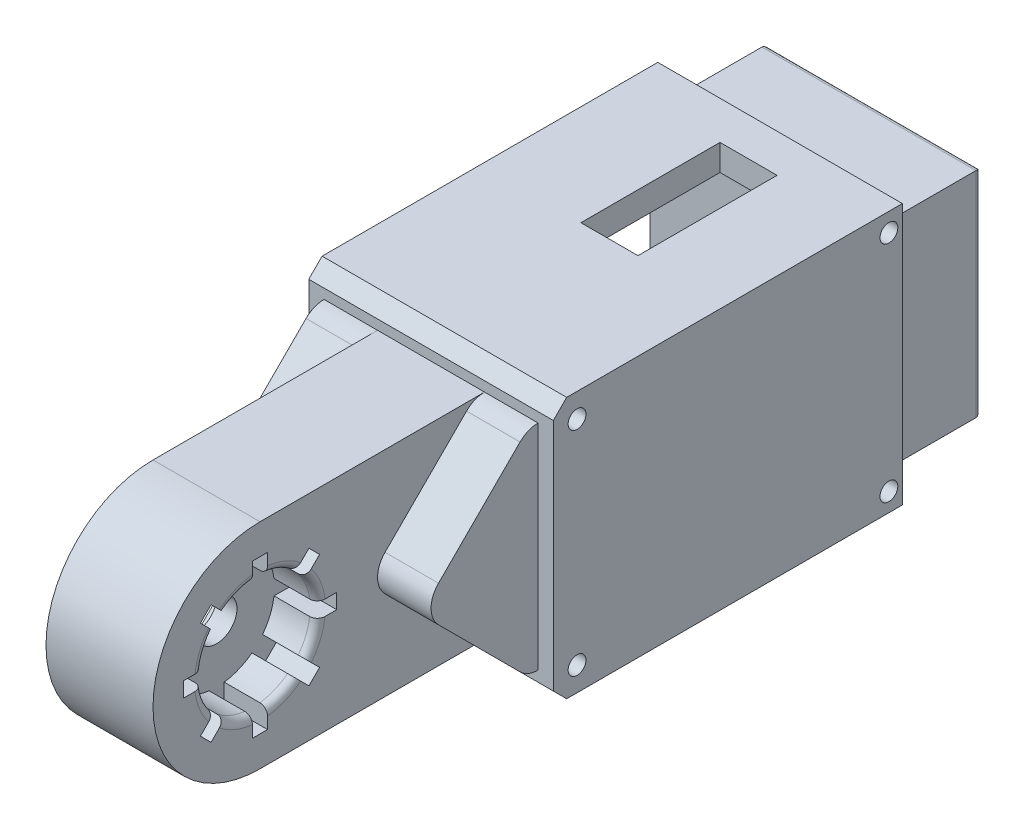
SolidWorks part; units mm, degrees
ref_plane "Front Plane" through (0, 0, 0) normal (0, 0, 1) x (1, 0, 0)
ref_plane "Top Plane" through (0, 0, 0) normal (0, 1, 0) x (1, 0, 0)
ref_plane "Right Plane" through (0, 0, 0) normal (1, 0, 0) x (0, 0, -1)
sketch "Sketch2" plane through (0, 0, 0) normal (0, 0, 1) x (1, 0, 0)
  line L1 (-21, 21) -> (21, 21)
  line L2 (-21, 21) -> (-21, -21)
  line L3 (-21, -21) -> (21, -21)
  line L4 (21, 21) -> (21, -21)
  line L5 (-21, 21) -> (21, -21) construction
  line L6 (-21, -21) -> (21, 21) construction
  point P0 (0, 0)
  dimension "D1" = 42
  dimension "D2" = 42
extrude "Boss-Extrude1" add sketch "Sketch2" along normal blind 89
ref_plane "Plane1" through (0, 0, 89) normal (0, 0, 1) x (1, 0, 0)
sketch "Sketch3" plane through (0, 0, 89) normal (0, 0, 1) x (1, 0, 0)
  line L0 (21, 21) -> (-21, 21) construction
  line L1 (10.5, -21) -> (-10.5, -21)
  line L2 (10.5, -21) -> (10.5, 21)
  line L3 (10.5, 21) -> (-10.5, 21)
  line L4 (-10.5, -21) -> (-10.5, 21)
  line L5 (10.5, -21) -> (-10.5, 21) construction
  line L6 (10.5, 21) -> (-10.5, -21) construction
  point P0 (0, 0)
  dimension "D1" = 21
ref_plane "Plane4" through (0, 0, 0) normal (0, 0, -1) x (-1, 0, 0)
extrude "Boss-Extrude2" add sketch "Sketch3" along normal blind 42
ref_plane "Plane5" through (-10.5, 0, 0) normal (-1, 0, 0) x (0, 0, 1)
sketch "Sketch8" plane through (-10.5, 0, 0) normal (-1, 0, 0) x (0, 0, 1)
  line L0 (131, 21) -> (131, -21) construction
  line L1 (131, 21) -> (131, -21)
  arc A0 (131, 21) -> (131, -21) centre (131, 0) cw
  dimension "D1" = 21
extrude "Boss-Extrude3" add sketch "Sketch8" against normal blind 21
ref_plane "Plane6" through (-10.5, 0, 0) normal (-1, 0, 0) x (0, 0, 1)
sketch "Sketch9" plane through (-10.5, 0, 0) normal (-1, 0, 0) x (0, 0, 1)
  line L0 (89, 21) -> (89, -21) construction
  line L1 (131, 21) -> (131, -21)
  circle A0 centre (131, 0) radius 11.35
  dimension "D1" = 42
  dimension "D2" = 22.7
extrude "Cut-Extrude2" cut sketch "Sketch9" against normal blind 8.5 contours A0
ref_plane "Plane7" through (10.5, 0, 0) normal (1, 0, 0) x (0, 0, -1)
sketch "Sketch11" plane through (10.5, 0, 0) normal (1, 0, 0) x (0, 0, -1)
  line L0 (-131, 21) -> (-131, -21)
  circle A0 centre (-131, 0) radius 11.35
  dimension "D1" = 22.7
extrude "Cut-Extrude3" cut sketch "Sketch11" against normal blind 8.5 contours A0
ref_plane "Plane8" through (-2, 0, 0) normal (-1, 0, 0) x (0, 0, 1)
sketch "Sketch12" plane through (-2, 0, 0) normal (-1, 0, 0) x (0, 0, 1)
  circle A0 centre (131, 0) radius 3.975
  dimension "D1" = 7.95
extrude "Cut-Extrude4" cut sketch "Sketch12" against normal through all
ref_plane "Plane10" through (-2, 0, 0) normal (-1, 0, 0) x (0, 0, 1)
ref_plane "Plane11" through (-10.5, 0, 0) normal (-1, 0, 0) x (0, 0, 1)
sketch "Sketch20" plane through (-10.5, 0, 0) normal (-1, 0, 0) x (0, 0, 1)
  line L0 (131, 0) -> (110, 0)
  line L1 (110, 0) -> (110, 21)
  line L2 (110, 0) -> (110, -21)
  line L4 (110, 21) -> (89, 21)
  line L6 (110, -21) -> (89, -21)
  line L7 (89, 21) -> (110, 0)
  line L8 (89, -21) -> (110, 0)
  line L9 (89, 21) -> (89, -21)
  circle A0 centre (131, 0) radius 11.35
  dimension "D1" = 21
extrude "Boss-Extrude4" add sketch "Sketch20" along normal blind 10.5 and the other way blind 31.5 contours L7 L9 L8
fillet "Fillet1" radius 5 1 edges at (15.75, 0, 110)
fillet "Fillet2" radius 5 1 edges at (-15.75, 0, 110)
fillet "Fillet3" radius 5 1 edges at (-15.75, -21, 89)
fillet "Fillet4" radius 5 1 edges at (-15.75, 21, 89)
fillet "Fillet5" radius 5 1 edges at (15.75, -21, 89)
fillet "Fillet6" radius 5 1 edges at (15.75, 21, 89)
fillet "Fillet7" radius 1.5 1 edges at (-10.5, 0, 142.35)
fillet "Fillet8" radius 1.5 1 edges at (10.5, 0, 119.65)
sketch "Sketch21" plane through (-10.5, 0, 0) normal (-1, 0, 0) x (0, 0, 1)
  line L1 (129.5207, 10.6415) -> (132.4793, 10.6415)
  line L2 (129.5207, 10.6415) -> (129.5207, 15.0585)
  line L3 (129.5207, 15.0585) -> (132.4793, 15.0585)
  line L4 (132.4793, 10.6415) -> (132.4793, 15.0585)
  line L5 (129.5207, 10.6415) -> (132.4793, 15.0585) construction
  line L6 (129.5207, 15.0585) -> (132.4793, 10.6415) construction
  circle A0 centre (131, 0) radius 12.85 construction
  point P0 (131, 12.85)
  dimension "D1" = 4.417
extrude "Cut-Extrude5" cut sketch "Sketch21" against normal blind 8.5
pattern_circular "CirPattern2" count 8 over 360 about axis through (0, 0, 131) along (1, 0, 0) of "Cut-Extrude5"
ref_plane "Plane12" through (0, 21, 0) normal (0, 1, 0) x (1, 0, 0)
ref_plane "Plane13" through (10.5, 0, 0) normal (1, 0, 0) x (0, 0, -1)
ref_plane "Plane14" through (0, 0, 0) normal (1, 0, 0) x (0, 0, -1)
mirror "Mirror1" about plane through (0, 0, 0) normal (1, 0, 0) of "CirPattern2", "Cut-Extrude5"
ref_plane "Plane15" through (21, 0, 0) normal (1, 0, 0) x (0, 0, -1)
sketch "Sketch24" plane through (21, 0, 0) normal (1, 0, 0) x (0, 0, -1)
  line L1 (-86.9289, 21) -> (0, 21)
  line L2 (-86.9289, 21) -> (-86.9289, 25.5452)
  line L3 (-86.9289, 25.5452) -> (0, 25.5452)
  line L4 (0, 21) -> (0, 25.5452)
  line L5 (-86.9289, -21) -> (0, -21)
  line L6 (-86.9289, -21) -> (-86.9289, -25.6891)
  line L7 (-86.9289, -25.6891) -> (0, -25.6891)
  line L8 (0, -21) -> (0, -25.6891)
extrude "Boss-Extrude6" add sketch "Sketch24" against normal blind 42
sketch "Sketch25" plane through (21, 0, 0) normal (1, 0, 0) x (0, 0, -1)
  line L0 (-18.4289, -25.6891) -> (-18.4289, 25.5452)
  line L1 (-86.9289, 25.5452) -> (-18.4289, 25.5452)
  line L2 (-86.9289, 25.5452) -> (-86.9289, -25.6891)
  line L3 (-86.9289, -25.6891) -> (-18.4289, -25.6891)
  dimension "D1" = 68.5
extrude "Boss-Extrude7" add sketch "Sketch25" along normal blind 3
ref_plane "Plane18" through (0, 0, 0) normal (0, 0, -1) x (-1, 0, 0)
ref_plane "Plane19" through (-21, 0, 0) normal (-1, 0, 0) x (0, 0, 1)
sketch "Sketch28" plane through (-21, 0, 0) normal (-1, 0, 0) x (0, 0, 1)
  line L0 (86.9289, -25.6891) -> (0, -25.6891) construction
  line L1 (86.9289, 25.5452) -> (18.4289, 25.5452)
  line L2 (86.9289, 25.5452) -> (86.9289, -25.6891)
  line L3 (86.9289, -25.6891) -> (18.4289, -25.6891)
  line L4 (18.4289, 25.5452) -> (18.4289, -25.6891)
  dimension "D1" = 68.5
extrude "Boss-Extrude8" add sketch "Sketch28" along normal blind 3
ref_plane "Plane20" through (-24, 0, 0) normal (-1, 0, 0) x (0, 0, 1)
sketch "Sketch30" plane through (-24, 0, 0) normal (-1, 0, 0) x (0, 0, 1)
  line L1 (81.9289, 20.4302) -> (19.9289, 20.4302)
  line L2 (81.9289, 20.4302) -> (81.9289, -20.5741)
  line L3 (81.9289, -20.5741) -> (19.9289, -20.5741)
  line L4 (19.9289, 20.4302) -> (19.9289, -20.5741)
  line L5 (81.9289, 20.4302) -> (19.9289, -20.5741) construction
  line L6 (81.9289, -20.5741) -> (19.9289, 20.4302) construction
  line L8 (86.9289, 25.5452) -> (18.4289, 25.5452) construction
  line L9 (18.4289, -25.6891) -> (86.9289, -25.6891) construction
  line L10 (86.9289, -21) -> (86.9289, 21) construction
  point P0 (50.9289, -0.0719)
  dimension "D1" = 5.115
  dimension "D2" = 5.115
  dimension "D3" = 62
  dimension "D4" = 5
extrude "Cut-Extrude6" cut sketch "Sketch30" against normal blind 45
ref_plane "Plane21" through (21, 0, 0) normal (1, 0, 0) x (0, 0, -1)
sketch "Sketch31" plane through (21, 0, 0) normal (1, 0, 0) x (0, 0, -1)
  line L0 (0, -25.6891) -> (0, 25.5452) construction
  line L1 (-18.4289, -25.6891) -> (0, -25.6891)
  line L2 (-18.4289, -25.6891) -> (-18.4289, -21.0741)
  line L3 (-18.4289, -21.0741) -> (0, -21.0741)
  line L4 (0, -25.6891) -> (0, -21.0741)
  line L6 (-18.4289, 25.5452) -> (0, 25.5452)
  line L7 (-18.4289, 25.5452) -> (-18.4289, 20.9302)
  line L8 (-18.4289, 20.9302) -> (0, 20.9302)
  line L9 (0, 25.5452) -> (0, 20.9302)
  dimension "D1" = 4.615
  dimension "D2" = 4.615
extrude "Cut-Extrude7" cut sketch "Sketch31" against normal through all
chamfer "Chamfer1" distance 1.5 angle 45 4 edges at (0, 20.9302, 18.4289) (21, -0.0719, 18.4289) (0, -21.0741, 18.4289) (-21, -0.0719, 18.4289)
ref_plane "Plane22" through (0, 0, 0) normal (0, 0, -1) x (-1, 0, 0)
sketch "Sketch32" plane through (0, 0, 0) normal (0, 0, -1) x (-1, 0, 0)
  line L1 (15, 15) -> (-15, 15)
  line L2 (15, 15) -> (15, -15)
  line L3 (15, -15) -> (-15, -15)
  line L4 (-15, 15) -> (-15, -15)
  line L5 (15, 15) -> (-15, -15) construction
  line L6 (15, -15) -> (-15, 15) construction
  point P0 (0, 0)
  dimension "D1" = 30
  dimension "D2" = 30
extrude "Cut-Extrude8" cut sketch "Sketch32" against normal blind 15
ref_plane "Plane23" through (0, 0, 19.9289) normal (0, 0, 1) x (1, 0, 0)
sketch "Sketch33" plane through (0, 0, 19.9289) normal (0, 0, 1) x (1, 0, 0)
  circle A0 centre (0, 0) radius 5
  dimension "D1" = 10
extrude "Cut-Extrude9" cut sketch "Sketch33" against normal blind 16.8
ref_plane "Plane24" through (-21, 0, 0) normal (-1, 0, 0) x (0, 0, 1)
sketch "Sketch34" plane through (-24, 0, 0) normal (-1, 0, 0) x (0, 0, 1)
  line L0 (86.9289, -0.0719) -> (103.6427, -0.0719) construction
  line L2 (88.3304, -21.6696) -> (88.3304, -28.2221)
  line L3 (88.3304, -28.2221) -> (81.7779, -28.2221)
  line L4 (81.7779, -28.2221) -> (88.3304, -21.6696)
  line L5 (86.9289, -25.6891) -> (86.9289, 25.5452) construction
  line L6 (88.3304, 28.0782) -> (81.7779, 28.0782)
  line L7 (88.3304, 21.5257) -> (88.3304, 28.0782)
  line L8 (81.7779, 28.0782) -> (88.3304, 21.5257)
extrude "Cut-Extrude10" cut sketch "Sketch34" against normal through all
chamfer "Chamfer2" distance 6 angle 45 1 edges at (-1.5, 20.4302, 81.9289)
chamfer "Chamfer3" distance 6 angle 45 1 edges at (-1.5, -20.5741, 81.9289)
chamfer "Chamfer4" distance 6 angle 45 1 edges at (-1.5, 20.4302, 19.9289)
chamfer "Chamfer5" distance 6 angle 45 1 edges at (-1.5, -20.5741, 19.9289)
sketch "Sketch35" plane through (-24, 0, 0) normal (-1, 0, 0) x (0, 0, 1)
  line L0 (78.9289, -17.5741) -> (85.6199, -24.3801) construction
  line L1 (82.2744, 20.8332) -> (85.6199, 24.2362) construction
  line L2 (81.9289, -14.5741) -> (75.9289, -20.5741) construction
  line L3 (84.3109, -25.6891) -> (86.9289, -23.0711) construction
  line L4 (78.9289, 17.4302) -> (85.6199, 24.2362) construction
  line L5 (75.9289, 20.4302) -> (81.9289, 14.4302) construction
  line L6 (86.9289, 22.9272) -> (84.3109, 25.5452) construction
  line L7 (18.4289, 25.5452) -> (21.0741, 21.9048) construction
  line L9 (18.4289, -25.6891) -> (21.074, -22.0485) construction
  line L10 (18.4289, 25.5452) -> (18.4289, -25.6891) construction
  circle A0 centre (21.0741, 21.9048) radius 1.75
  circle A1 centre (82.2744, 20.8332) radius 1.75
  circle A2 centre (82.2744, -20.9771) radius 1.75
  circle A3 centre (21.074, -22.0485) radius 1.75
  dimension "D5" = 3.5
  dimension "D1" = 36.003
  dimension "D2" = 36
  dimension "D3" = 4.5
  dimension "D4" = 4.5
extrude "Cut-Extrude11" cut sketch "Sketch35" against normal through all
ref_plane "Plane26" through (0, -25.6891, 0) normal (0, -1, 0) x (-1, 0, 0)
sketch "Sketch38" plane through (0, -25.6891, 0) normal (0, -1, 0) x (-1, 0, 0)
  line L0 (-24, -18.4289) -> (24, -18.4289) construction
  line L1 (4.2922, -53.2289) -> (-6.9078, -53.2289)
  line L2 (4.2922, -53.2289) -> (4.2922, -25.9289)
  line L3 (4.2922, -25.9289) -> (-6.9078, -25.9289)
  line L4 (-6.9078, -53.2289) -> (-6.9078, -25.9289)
  dimension "D1" = 7.5
  dimension "D2" = 27.3
  dimension "D3" = 11.2
extrude "Cut-Extrude12" cut sketch "Sketch38" against normal through all
fillet "Fillet9" radius 1 4 edges at (21, -0.0719, 0) (0, 20.9302, 0) (0, -21.0741, 0) (-21, -0.0719, 0)
fillet "Fillet10" radius 1 4 edges at (0, 15, 0) (15, 0, 0) (0, -15, 0) (-15, 0, 0)
